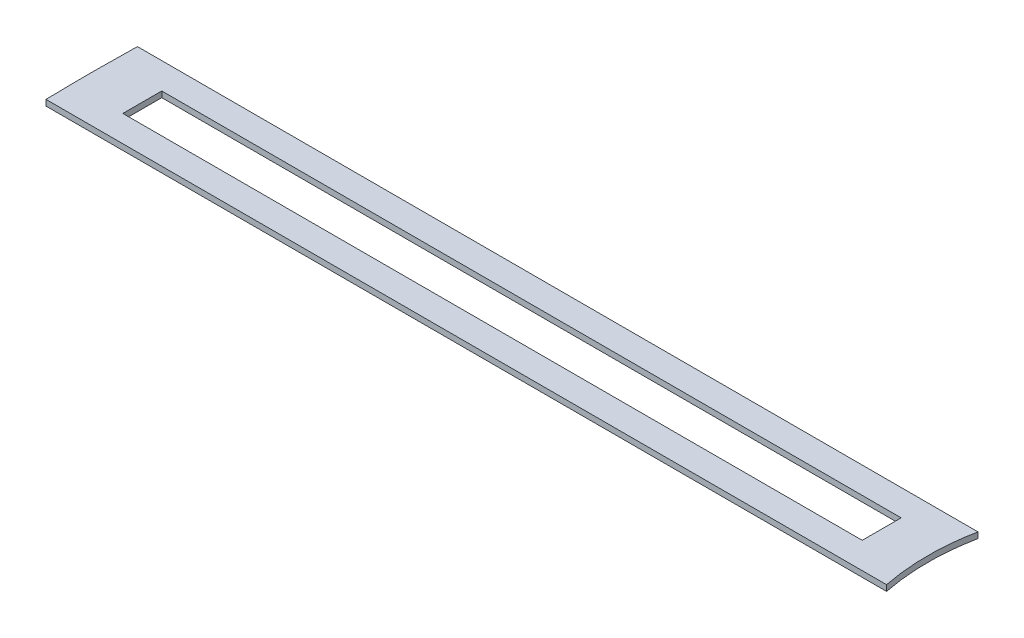
SolidWorks part; units mm, degrees
ref_plane "Front Plane" through (0, 0, 0) normal (0, 0, 1) x (1, 0, 0)
ref_plane "Top Plane" through (0, 0, 0) normal (0, 1, 0) x (1, 0, 0)
ref_plane "Right Plane" through (0, 0, 0) normal (1, 0, 0) x (0, 0, -1)
sketch "Sketch1" plane through (0, 0, 0) normal (0, 1, 0) x (1, 0, 0)
  line L0 (216, -23.5) -> (-216, -23.5)
  line L1 (-216, 23.5) -> (216, 23.5)
  line L2 (-250.8091, 0) -> (354.3866, 0) construction
  line L4 (-190, -10) -> (190, -10)
  line L5 (-190, -10) -> (-190, 10)
  line L6 (-190, 10) -> (190, 10)
  line L7 (190, -10) -> (190, 10)
  line L8 (-190, -10) -> (190, 10) construction
  line L9 (-190, 10) -> (190, -10) construction
  ellipse E0 centre (274.2314, 0) end of major axis (274.2314, -85.639) minor radius 60.5559 (216, 23.5) -> (216, -23.5) ccw
  ellipse E1 centre (278.2606, 0) end of major axis (278.2606, -699.385) minor radius 494.5398 (-216, 23.5) -> (-216, -23.5) ccw
  point P20 (0, 0)
  dimension "D1" = 216
  dimension "D2" = 216
  dimension "D3" = 23.5
  dimension "D4" = 23.5
  dimension "D5" = 20
  dimension "D6" = 380
extrude "Boss-Extrude1" add sketch "Sketch1" along normal mid plane 3
